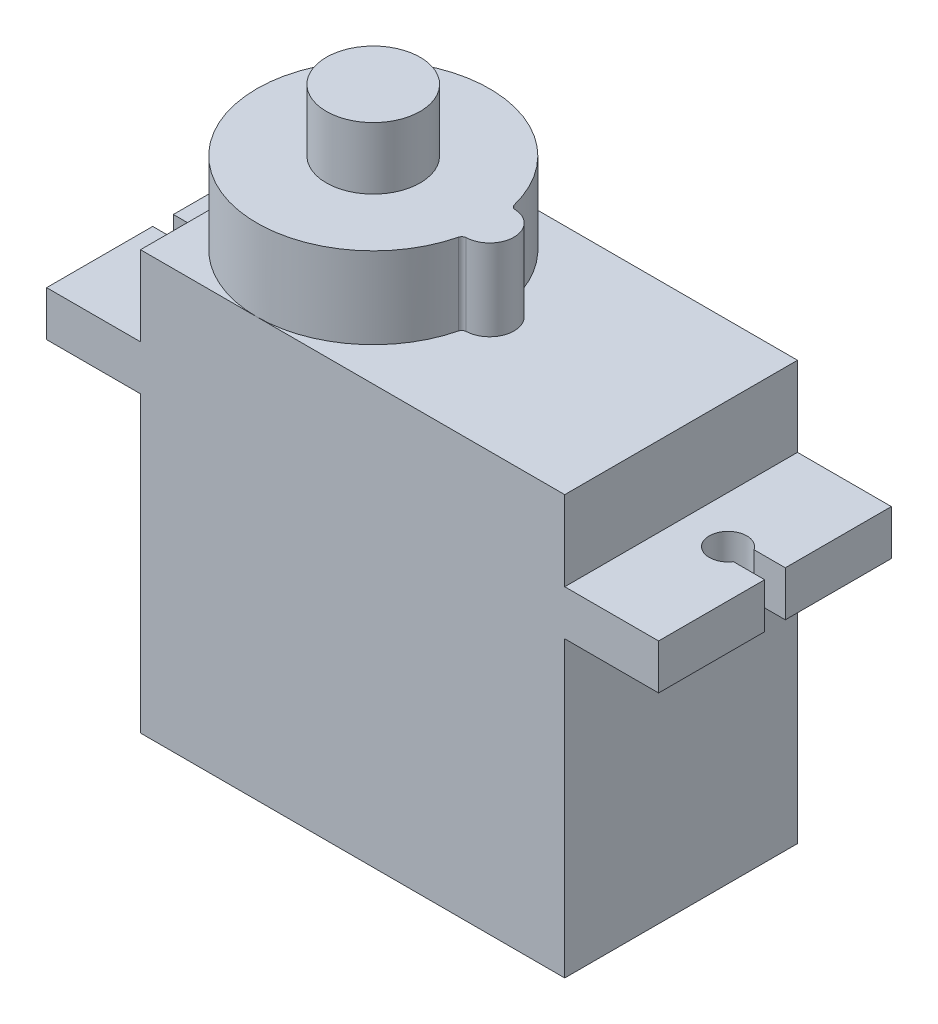
SolidWorks part; units mm, degrees
ref_plane "Front Plane" through (0, 0, 0) normal (0, 0, 1) x (1, 0, 0)
ref_plane "Top Plane" through (0, 0, 0) normal (0, 1, 0) x (1, 0, 0)
ref_plane "Right Plane" through (0, 0, 0) normal (1, 0, 0) x (0, 0, -1)
sketch "Sketch1" plane through (0, 0, 0) normal (0, 1, 0) x (1, 0, 0)
  line L1 (-11.3, 6.2) -> (11.3, 6.2)
  line L2 (-11.3, 6.2) -> (-11.3, -6.2)
  line L3 (-11.3, -6.2) -> (11.3, -6.2)
  line L4 (11.3, 6.2) -> (11.3, -6.2)
  line L5 (-11.3, 6.2) -> (11.3, -6.2) construction
  line L6 (-11.3, -6.2) -> (11.3, 6.2) construction
  point P0 (0, 0)
  dimension "D1" = 12.4
  dimension "D2" = 22.6
extrude "Boss-Extrude1" add sketch "Sketch1" along normal blind 22.3
sketch "Sketch2" plane through (0, 0, 6.2) normal (0, 0, 1) x (1, 0, 0)
  line L0 (11.3, 22.3) -> (11.3, 0) construction
  line L1 (11.3, 18.05) -> (16.3, 18.05)
  line L2 (11.3, 18.05) -> (11.3, 15.65)
  line L3 (11.3, 15.65) -> (16.3, 15.65)
  line L4 (16.3, 18.05) -> (16.3, 15.65)
  line L5 (-11.3, 22.3) -> (11.3, 22.3) construction
  line L6 (0, 0) -> (0, 7.7907) construction
  line L7 (-16.3, 18.05) -> (-16.3, 15.65)
  line L8 (-11.3, 15.65) -> (-16.3, 15.65)
  line L9 (-11.3, 18.05) -> (-11.3, 15.65)
  line L10 (-11.3, 18.05) -> (-16.3, 18.05)
  dimension "D1" = 2.4
  dimension "D2" = 5
  dimension "D3" = 4.25
extrude "Boss-Extrude2" add sketch "Sketch2" against normal up to vertex (12.4 mm away)
sketch "Sketch3" plane through (0, 18.05, 0) normal (0, 1, 0) x (1, 0, 0)
  line L0 (14.6352, 0.55) -> (16.3, 0.55)
  line L1 (16.3, 6.2) -> (16.3, -6.2) construction
  line L2 (16.3, 0.55) -> (16.3, -0.55)
  line L3 (16.3, -0.55) -> (14.6352, -0.55)
  line L4 (0, 0) -> (13.8, 0) construction
  circle A0 centre (13.8, 0) radius 1
  dimension "D1" = 2
  dimension "D3" = 2.5
  dimension "D2" = 1.1
extrude "s" cut sketch "Sketch3" against normal through all
mirror "Mirror1" about plane through (0, 0, 0) normal (1, 0, 0) of "s"
sketch "Sketch4" plane through (0, 22.3, 0) normal (0, 1, 0) x (1, 0, 0)
  line L0 (-11.3, 6.2) -> (-11.3, -6.2) construction
  line L1 (11.3, 6.2) -> (-11.3, 6.2) construction
  arc A0 (0.9186, 1.4888) -> (0.9186, -1.4888) centre (-5.1, 0) ccw
  arc A1 (1.1514, -1.299) -> (1.1514, 1.299) centre (1.1, 0) ccw
  arc A2 (1.1514, -1.299) -> (0.9186, -1.4888) centre (1.1613, -1.5488) ccw
  arc A3 (1.1514, 1.299) -> (0.9186, 1.4888) centre (1.1613, 1.5488) cw
  dimension "D1" = 12.4
  dimension "D2" = 2.6
  dimension "D3" = 0.25
extrude "Boss-Extrude3" add sketch "Sketch4" along normal blind 4.33
sketch "Sketch5" plane through (0, 26.63, 0) normal (0, 1, 0) x (1, 0, 0)
  circle A0 centre (-5.1, 0) radius 2.5
  dimension "D1" = 5
extrude "Boss-Extrude4" add sketch "Sketch5" along normal blind 3.3
sketch "Sketch6" plane through (-11.3, 0, 0) normal (-1, 0, 0) x (0, 0, 1)
  line L0 (-6.2, 0) -> (6.2, 0) construction
  circle A0 centre (0, 4.5) radius 0.6
  circle A1 centre (1.2, 4.5) radius 0.6
  circle A2 centre (-1.2, 4.5) radius 0.6
  point P6 (0, 0)
  dimension "D1" = 1.2
  dimension "D2" = 4.5
extrude "Boss-Extrude6" add sketch "Sketch6" along normal blind 2.3 separate body contours A1 | A0 | A2
